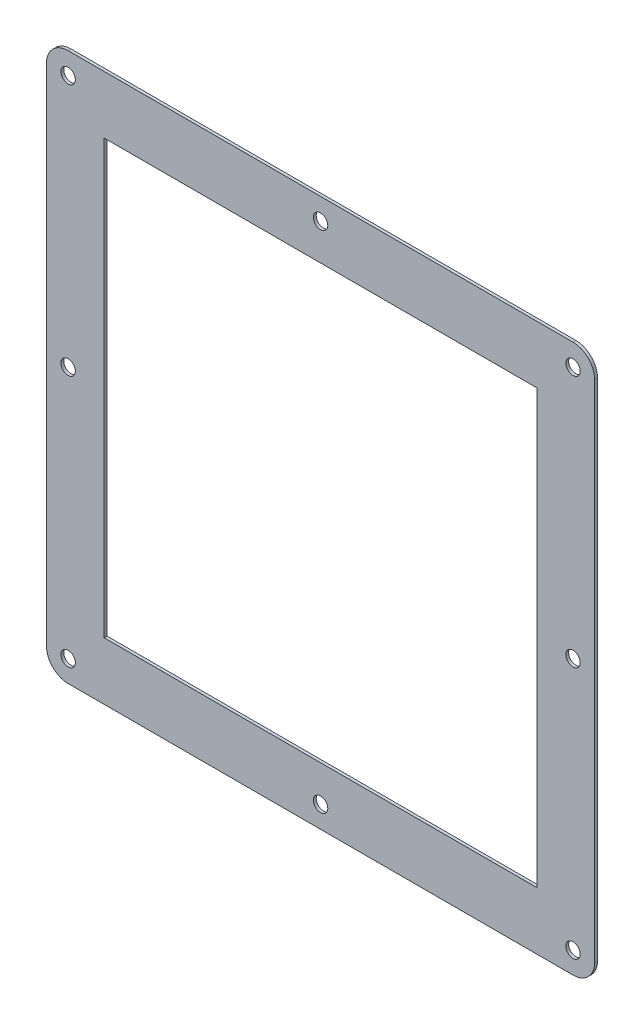
SolidWorks part; units mm, degrees
ref_plane "Front Plane" through (0, 0, 0) normal (0, 0, 1) x (1, 0, 0)
ref_plane "Top Plane" through (0, 0, 0) normal (0, 1, 0) x (1, 0, 0)
ref_plane "Right Plane" through (0, 0, 0) normal (1, 0, 0) x (0, 0, -1)
sketch "Sketch2" plane through (0, 0, 0) normal (0, 0, 1) x (1, 0, 0)
  line L0 (-175, 175) -> (175, 175) construction
  line L1 (-175, 190) -> (175, 190)
  line L2 (-190, 175) -> (-190, -175)
  line L3 (-175, -190) -> (175, -190)
  line L4 (190, 175) -> (190, -175)
  line L5 (-190, 190) -> (190, -190) construction
  line L6 (-190, -190) -> (190, 190) construction
  line L7 (175, 175) -> (175, -175) construction
  line L8 (175, -175) -> (-175, -175) construction
  line L9 (-175, -175) -> (-175, 175) construction
  line L11 (-150, 150) -> (150, 150)
  line L12 (-150, 150) -> (-150, -150)
  line L13 (-150, -150) -> (150, -150)
  line L14 (150, 150) -> (150, -150)
  line L15 (-150, 150) -> (150, -150) construction
  line L16 (-150, -150) -> (150, 150) construction
  arc A0 (-190, -175) -> (-175, -190) centre (-175, -175) ccw
  arc A1 (175, -190) -> (190, -175) centre (175, -175) ccw
  arc A2 (175, 190) -> (190, 175) centre (175, 175) cw
  arc A3 (-175, 190) -> (-190, 175) centre (-175, 175) ccw
  circle A4 centre (-175, 175) radius 5
  circle A5 centre (0, 175) radius 5
  circle A6 centre (175, 175) radius 5
  circle A14 centre (175, 0) radius 5
  circle A15 centre (-175, 0) radius 5
  circle A16 centre (-175, -175) radius 5
  circle A17 centre (0, -175) radius 5
  circle A18 centre (175, -175) radius 5
  point P0 (0, 0)
  point P26 (0, 0)
  dimension "D3" = 15
  dimension "D4" = 10
  dimension "D5" = 10
  dimension "D6" = 10
  dimension "D7" = 300
  dimension "D8" = 10
  dimension "D9" = 10
  dimension "D10" = 10
  dimension "D11" = 10
  dimension "D1" = 380
  dimension "D2" = 380
extrude "Boss-Extrude1" add sketch "Sketch2" along normal blind 2
